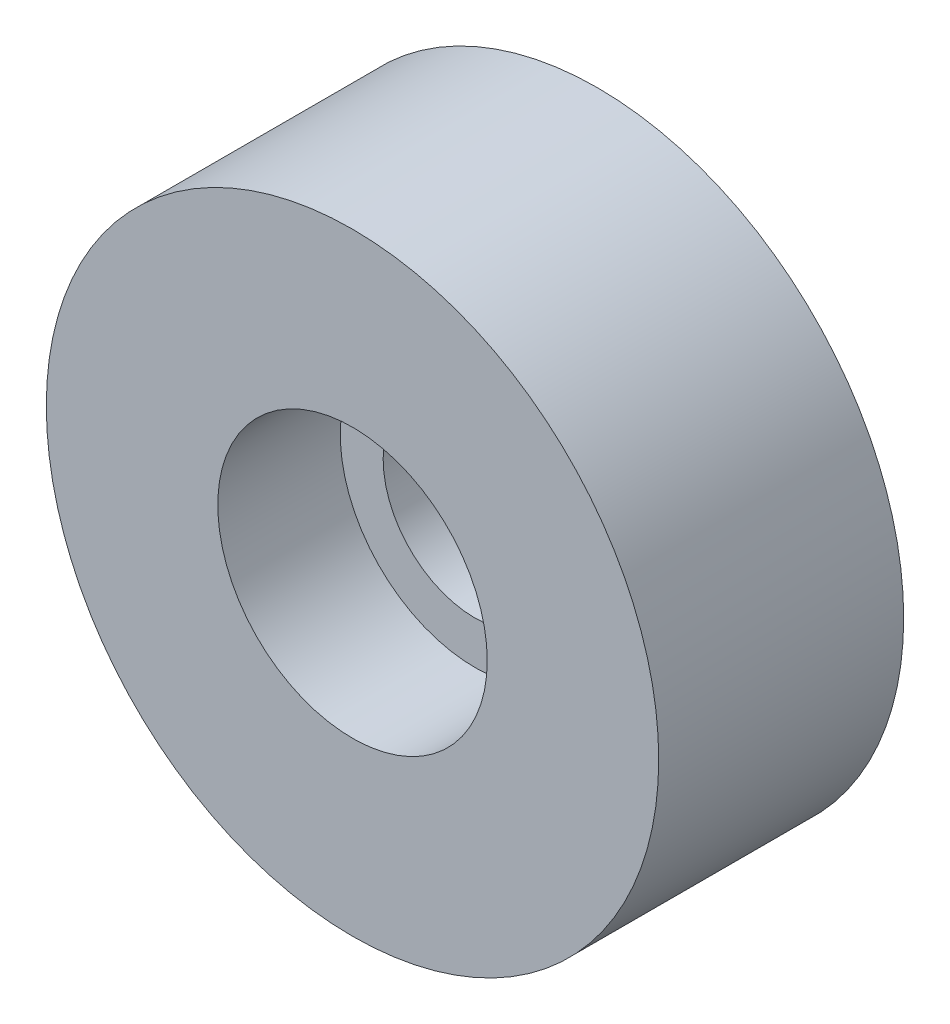
SolidWorks part; units mm, degrees
ref_plane "Plan de face" through (0, 0, 0) normal (0, 0, 1) x (1, 0, 0)
ref_plane "Plan de dessus" through (0, 0, 0) normal (0, 1, 0) x (1, 0, 0)
ref_plane "Plan de droite" through (0, 0, 0) normal (1, 0, 0) x (0, 0, -1)
sketch "Esquisse1" plane through (0, 0, 0) normal (0, 0, 1) x (1, 0, 0)
  circle A0 centre (0, 0) radius 5
  dimension "D1" = 10
extrude "Boss.-Extru.1" add sketch "Esquisse1" along normal blind 4
sketch "Esquisse2" plane through (0, 0, 4) normal (0, 0, 1) x (1, 0, 0)
  circle A0 centre (0, 0) radius 2.2
  dimension "D1" = 4.4
extrude "Enlèv. mat.-Extru.1" cut sketch "Esquisse2" against normal blind 2
sketch "Esquisse3" plane through (0, 0, 0) normal (0, 0, -1) x (-1, 0, 0)
  circle A0 centre (0, 0) radius 1.5
  dimension "D1" = 3
extrude "Enlèv. mat.-Extru.2" cut sketch "Esquisse3" against normal through all
